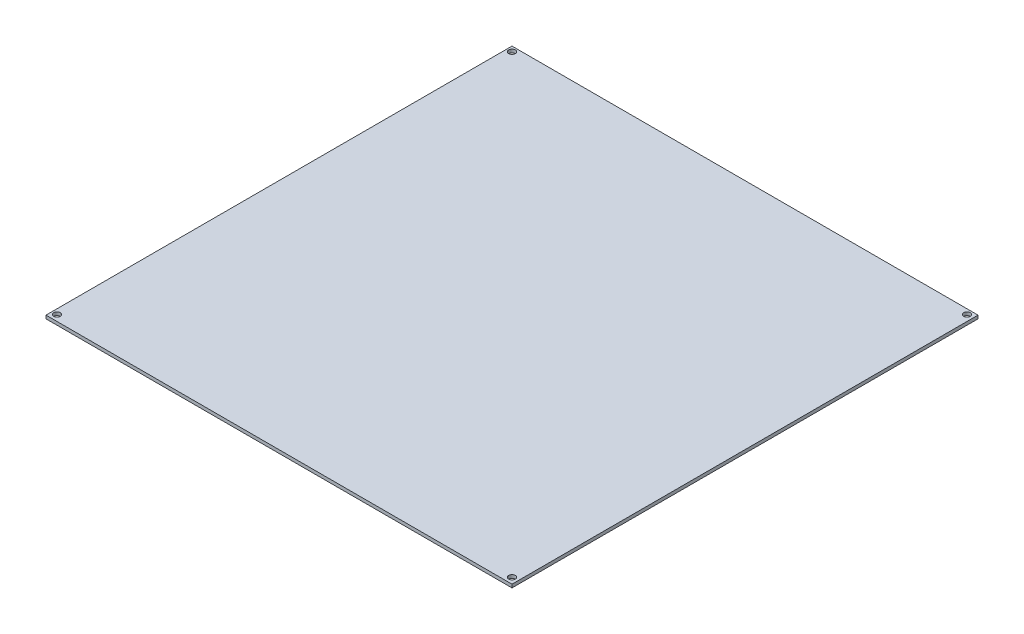
SolidWorks part; units mm, degrees
material "Placa de circuito impreso"
ref_plane "Alzado" through (0, 0, 0) normal (0, 0, 1) x (1, 0, 0)
ref_plane "Planta" through (0, 0, 0) normal (0, 1, 0) x (1, 0, 0)
ref_plane "Vista lateral" through (0, 0, 0) normal (1, 0, 0) x (0, 0, -1)
sketch "Croquis1" plane through (0, 0, 0) normal (0, 1, 0) x (1, 0, 0)
  line L1 (-125.0431, 61.6824) -> (88.9569, 61.6824)
  line L2 (-125.0431, 61.6824) -> (-125.0431, -152.3176)
  line L3 (-125.0431, -152.3176) -> (88.9569, -152.3176)
  line L4 (88.9569, 61.6824) -> (88.9569, -152.3176)
  circle A0 centre (-122.7931, 59.4324) radius 1.5
  circle A1 centre (86.2069, 59.4324) radius 1.5
  circle A2 centre (-122.7931, -149.5676) radius 1.5
  circle A3 centre (86.2069, -149.5676) radius 1.5
  dimension "D2" = 3
  dimension "D3" = 209
  dimension "D4" = 209
  dimension "D5" = 209
  dimension "D6" = 209
  dimension "D7" = 2.75
  dimension "D8" = 2.75
  dimension "D9" = 2.75
  dimension "D1" = 214
extrude "Saliente-Extruir2" add sketch "Croquis1" along normal blind 1.5
